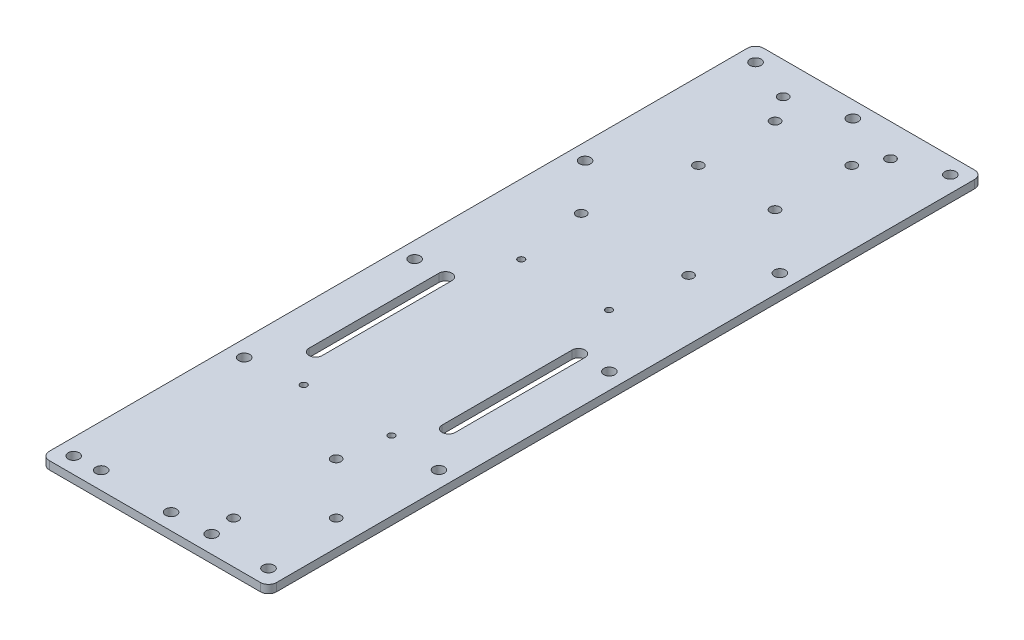
SolidWorks part; units mm, degrees
ref_plane "Front Plane" through (0, 0, 0) normal (0, 0, 1) x (1, 0, 0)
ref_plane "Top Plane" through (0, 0, 0) normal (0, 1, 0) x (1, 0, 0)
ref_plane "Right Plane" through (0, 0, 0) normal (1, 0, 0) x (0, 0, -1)
sketch "Sketch2" plane through (0, 0, 0) normal (0, 1, 0) x (1, 0, 0)
  line L0 (-44.45, 0) -> (44.45, 0) construction
  line L1 (-41.275, 139.7) -> (41.275, 139.7)
  line L2 (-44.45, 136.525) -> (-44.45, -136.525)
  line L3 (-41.275, -139.7) -> (41.275, -139.7)
  line L4 (44.45, 136.525) -> (44.45, -136.525)
  line L5 (0, 139.7) -> (0, -139.7) construction
  arc A0 (-44.45, -136.525) -> (-41.275, -139.7) centre (-41.275, -136.525) ccw
  arc A1 (41.275, -139.7) -> (44.45, -136.525) centre (41.275, -136.525) ccw
  arc A2 (41.275, 139.7) -> (44.45, 136.525) centre (41.275, 136.525) cw
  arc A3 (-41.275, 139.7) -> (-44.45, 136.525) centre (-41.275, 136.525) ccw
  point P8 (0, 0)
  point P13 (-44.45, -139.7)
  point P16 (44.45, -139.7)
  point P21 (-44.45, 139.7)
  dimension "D3" = 3.175
  dimension "D1" = 279.4
  dimension "D2" = 88.9
extrude "Plate Thickness" add sketch "Sketch2" along normal blind 3.175 contours L2 A0 L3 A1 L4 A2 L1 A3
sketch "Sketch3" plane through (0, 3.175, 0) normal (0, 1, 0) x (1, 0, 0)
  line L0 (-44.45, 136.525) -> (-44.45, -136.525) construction
  line L1 (-41.275, 139.7) -> (41.275, 139.7) construction
  line L4 (0, 139.7) -> (0, -139.7) construction
  line L5 (-41.275, -139.7) -> (41.275, -139.7) construction
  circle A0 centre (-38.1, 133.35) radius 2.159
  circle A1 centre (-38.1, 66.675) radius 2.159
  circle A2 centre (-38.1, -66.675) radius 2.159
  circle A3 centre (-38.1, -133.35) radius 2.159
  circle A4 centre (38.1, -133.35) radius 2.159
  circle A5 centre (38.1, -66.675) radius 2.159
  circle A6 centre (38.1, 66.675) radius 2.159
  circle A7 centre (38.1, 133.35) radius 2.159
  circle A8 centre (0, 133.35) radius 2.159
  circle A9 centre (0, -133.35) radius 2.159
  circle A10 centre (-38.1, 0) radius 2.159
  circle A11 centre (38.1, 0) radius 2.159
  dimension "D1" = 4.318
  dimension "D4" = 4.318
  dimension "D2" = 6.35
  dimension "D3" = 6.35
  dimension "D5" = 66.675
  dimension "D6" = 6.35
  dimension "D7" = 66.675
extrude "Mounting holes" cut sketch "Sketch3" against normal through all
sketch "Sketch4" plane through (0, 3.175, 0) normal (0, 1, 0) x (1, 0, 0)
  line L0 (-21.0058, 48.0812) -> (21.0058, 48.0812) construction
  line L1 (0, 0) -> (0, 139.7) construction
  line L4 (-41.275, 139.7) -> (41.275, 139.7) construction
  circle A0 centre (-21.0058, 127.0752) radius 1.905
  circle A1 centre (-21.0058, 48.0812) radius 1.905
  circle A2 centre (21.0058, 48.0812) radius 1.905
  circle A3 centre (21.0058, 127.0752) radius 1.905
  point P13 (0, 48.0812)
  point P17 (0, 69.85)
  point P18 (0, 69.85)
  dimension "D1" = 3.81
  dimension "D2" = 78.994
  dimension "D3" = 42.0116
extrude "Jetson Holes (w/ mount)" cut sketch "Sketch4" against normal through all
sketch "Sketch5" plane through (0, 3.175, 0) normal (0, 1, 0) x (1, 0, 0)
  circle A1 centre (-14.3419, 117.2351) radius 1.905
  circle A3 centre (15.6555, 117.2351) radius 1.905
  circle A4 centre (15.6555, 87.2377) radius 1.905
  circle A5 centre (-14.3419, 87.2377) radius 1.905
  dimension "D1" = 3.81
  dimension "D2" = 29.9974
  dimension "D3" = 29.9974
extrude "PDB holes" cut sketch "Sketch5" against normal through all
sketch "Sketch6" plane through (0, 3.175, 0) normal (0, 1, 0) x (1, 0, 0)
  line L0 (44.45, 136.525) -> (44.45, -136.525) construction
  circle A6 centre (34.29, -103.0828) radius 1.905
  circle A7 centre (14.224, -83.0168) radius 1.905
  circle A8 centre (14.224, -123.1488) radius 1.905
  dimension "D1" = 10.16
  dimension "D5" = 3.81
  dimension "D6" = 40.132
  dimension "D7" = 20.066
  dimension "D8" = 20.066
extrude "Lidar Holes" cut sketch "Sketch6" against normal through all
sketch "Sketch7" plane through (0, 3.175, 0) normal (0, 1, 0) x (1, 0, 0)
  line L0 (0, 139.7) -> (0, -139.7) construction
  line L1 (-41.275, 139.7) -> (41.275, 139.7) construction
  line L2 (-41.275, -139.7) -> (41.275, -139.7) construction
  line L3 (17.145, 20.7699) -> (-17.145, 20.7699) construction
  circle A0 centre (-17.145, 20.7699) radius 1.27
  circle A1 centre (-17.145, -64.3201) radius 1.27
  circle A2 centre (17.145, -64.3201) radius 1.27
  circle A3 centre (17.145, 20.7699) radius 1.27
  point P14 (0, 20.7699)
  dimension "D1" = 2.54
  dimension "D2" = 85.09
  dimension "D3" = 34.29
extrude "PixHawk Holes" cut sketch "Sketch7" against normal through all
sketch "Sketch8" plane through (0, 3.175, 0) normal (0, 1, 0) x (1, 0, 0)
  line L0 (0, 139.7) -> (0, -115.5095) construction
  line L1 (-41.275, 139.7) -> (41.275, 139.7) construction
  line L2 (-26.035, -0.006) -> (-26.035, -50.806) construction
  line L3 (-23.495, -0.006) -> (-23.495, -50.806)
  line L4 (-28.575, -0.006) -> (-28.575, -50.806)
  line L5 (26.035, -0.006) -> (26.035, -50.806) construction
  line L6 (23.495, -0.006) -> (23.495, -50.806)
  line L7 (28.575, -0.006) -> (28.575, -50.806)
  arc A0 (-23.495, -0.006) -> (-28.575, -0.006) centre (-26.035, -0.006) ccw
  arc A1 (-28.575, -50.806) -> (-23.495, -50.806) centre (-26.035, -50.806) ccw
  arc A2 (23.495, -0.006) -> (28.575, -0.006) centre (26.035, -0.006) cw
  arc A3 (28.575, -50.806) -> (23.495, -50.806) centre (26.035, -50.806) cw
  point P7 (-26.035, -25.406)
  point P14 (26.035, -25.406)
  dimension "D1" = 50.8
  dimension "D2" = 5.08
  dimension "D3" = 26.035
extrude "Battery Holes" cut sketch "Sketch8" against normal through all
sketch "Sketch9" plane through (0, 3.175, 0) normal (0, 1, 0) x (1, 0, 0)
  circle A0 centre (-27.8687, -132.8308) radius 2.159
  circle A1 centre (15.3113, -132.8308) radius 2.159
  dimension "D1" = 4.318
  dimension "D2" = 4.318
  dimension "D3" = 43.18
extrude "Cut-Extrude1" cut sketch "Sketch9" against normal through all
